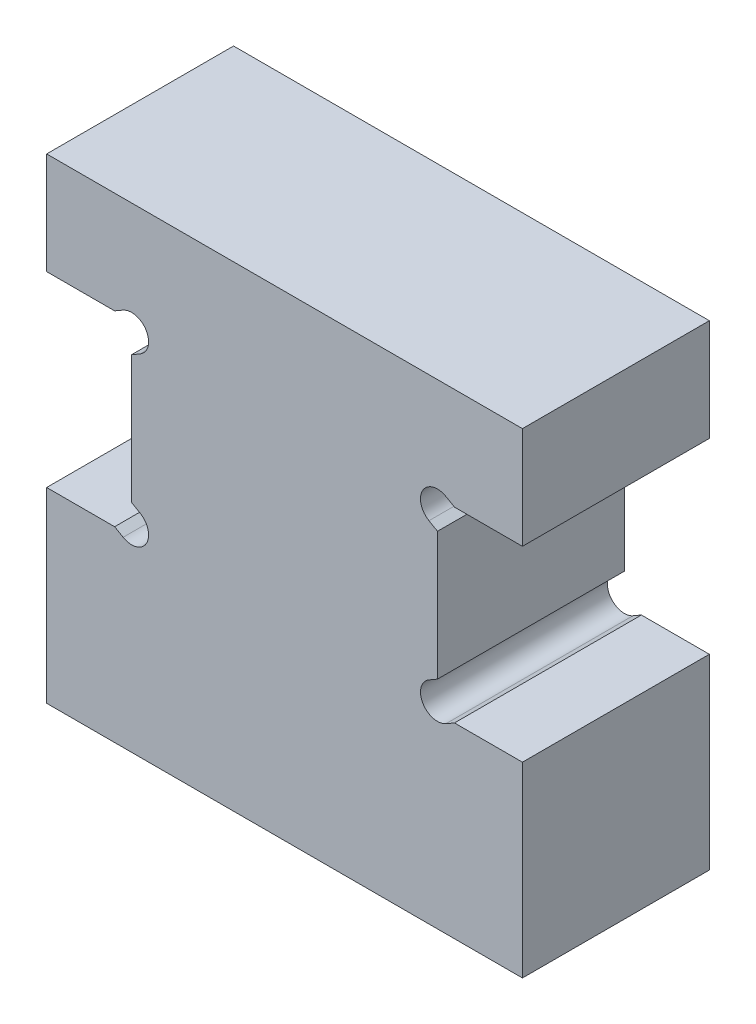
SolidWorks part; units mm, degrees
ref_plane "Piano frontale" through (0, 0, 0) normal (0, 0, 1) x (1, 0, 0)
ref_plane "Piano superiore" through (0, 0, 0) normal (0, 1, 0) x (1, 0, 0)
ref_plane "Piano destro" through (0, 0, 0) normal (1, 0, 0) x (0, 0, -1)
sketch "Sketch1" plane through (0, 0, 0) normal (0, 0, 1) x (1, 0, 0)
  line L0 (0, 44.6547) -> (0, -43.8643) construction
  line L1 (14, -15.9397) -> (-14, -15.9397)
  line L2 (-14, -15.9397) -> (-14, -4.9397)
  line L3 (-14, -4.9397) -> (-10, -4.9397)
  line L4 (-26.6336, 0.5603) -> (10.3486, 0.5603) construction
  line L5 (-10, -4.9397) -> (-9.5, -5.2283)
  line L6 (-8.5, 4.6169) -> (-9, 4.3283)
  line L7 (-8.5, -3.4963) -> (-9, -3.2076)
  line L8 (-9, -3.2076) -> (-9, 4.3283)
  line L9 (-10, 6.0603) -> (-9.5, 6.349)
  line L10 (-14, 6.0603) -> (-10, 6.0603)
  line L11 (-14, 6.0603) -> (-14, 12.0603)
  line L12 (-14, 12.0603) -> (14, 12.0603)
  line L13 (14, 6.0603) -> (14, 12.0603)
  line L14 (14, 6.0603) -> (10, 6.0603)
  line L15 (10, 6.0603) -> (9.5, 6.349)
  line L16 (9, -3.2076) -> (9, 4.3283)
  line L17 (8.5, -3.4963) -> (9, -3.2076)
  line L18 (8.5, 4.6169) -> (9, 4.3283)
  line L19 (10, -4.9397) -> (9.5, -5.2283)
  line L20 (14, -4.9397) -> (10, -4.9397)
  line L21 (14, -15.9397) -> (14, -4.9397)
  arc A0 (-9.5, -5.2283) -> (-8.5, -3.4963) centre (-9, -4.3623) ccw
  arc A1 (-9.5, 6.349) -> (-8.5, 4.6169) centre (-9, 5.483) cw
  arc A2 (9.5, 6.349) -> (8.5, 4.6169) centre (9, 5.483) ccw
  arc A3 (9.5, -5.2283) -> (8.5, -3.4963) centre (9, -4.3623) cw
  point P3 (9, 0.5603)
  point P18 (-9, 0.5603)
  point P29 (0, 12.0603)
  point P36 (0, -15.9397)
  dimension "D3" = 5
  dimension "D2" = 1
  dimension "D1" = 30
  dimension "D4" = 14
  dimension "D5" = 11
  dimension "D6" = 5.5
  dimension "D7" = 6
extrude "Boss-Extrude1" add sketch "Sketch1" along normal blind 11
sketch "Sketch2" plane through (0, -15.9397, 0) normal (0, -1, 0) x (1, 0, 0)
  line L2 (-14, 11) -> (14, 11) construction
  line L3 (-14, 11) -> (14, 11)
  line L4 (-14, 11) -> (-14, 0) construction
  line L5 (-14, 11) -> (-14, 0)
  line L6 (14, 11) -> (14, 0) construction
  line L7 (-14, 0) -> (14, 0) construction
  line L8 (14, 11) -> (14, 0)
  line L9 (-14, 0) -> (14, 0)
  circle A0 centre (0, 5.5) radius 2.166
hole_wizard "M5 Tapped Hole1" positions "Sketch4" profile "Sketch5" tap size "M5" standard "ISO"
sketch "Sketch4" plane through (0, -15.9397, 0) normal (0, -1, 0) x (-1, 0, 0)
  point P0 (0, -5.5)
sketch "Sketch5" plane through (0, -15.9397, 5.5) normal (1, 0, 0) x (0, 0, -1)
  line L0 (0, 0) -> (0, 18)
  line L1 (0, 18) -> (2.1, 16.7382)
  line L2 (2.1, 16.7382) -> (2.1, 0)
  line L5 (2.1, 0) -> (0, 0)
  line L10 (0, 18) -> (-2.1, 16.7382) construction
  line L11 (0, -6.35) -> (0, 107.95) construction
  dimension "Tap Drill Dia." = 4.2
  dimension "Tap Drill Depth" = 18
  dimension "Drill Angle" = 118
cosmetic thread "Hole Thread1" parameters "D1"=14, "D2"=5
